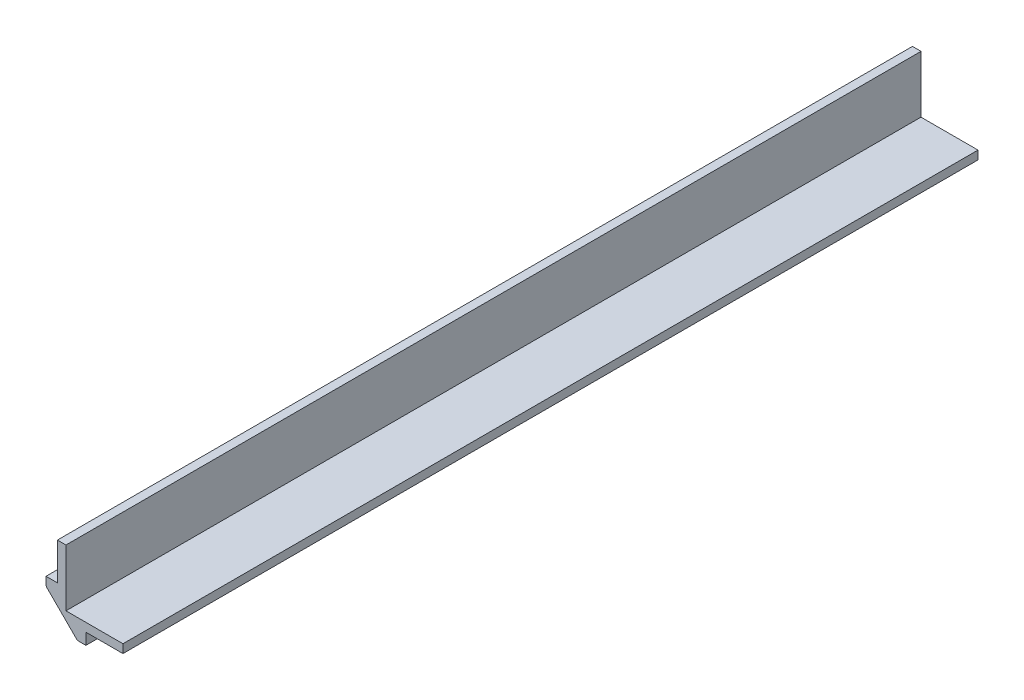
SolidWorks part; units mm, degrees
ref_plane "Front Plane" through (0, 0, 0) normal (0, 0, 1) x (1, 0, 0)
ref_plane "Top Plane" through (0, 0, 0) normal (0, 1, 0) x (1, 0, 0)
ref_plane "Right Plane" through (0, 0, 0) normal (1, 0, 0) x (0, 0, -1)
ref_plane "Plane1" through (0, 0, 280) normal (0, 0, 1) x (1, 0, 0)
sketch "Sketch1" plane through (0, 0, 280) normal (0, 0, 1) x (1, 0, 0)
  line L0 (-7, 4) -> (4, -7)
  line L1 (4, -7) -> (7, -7)
  line L2 (7, -7) -> (7, -3)
  line L3 (7, -3) -> (20, -3)
  line L4 (20, -3) -> (20, 0)
  line L5 (20, 0) -> (0, 0)
  line L6 (0, 0) -> (0, 20)
  line L7 (0, 20) -> (-3, 20)
  line L8 (-3, 20) -> (-3, 7)
  line L9 (-3, 7) -> (-7, 7)
  line L10 (-7, 7) -> (-7, 4)
extrude "Boss-Extrude1" add sketch "Sketch1" against normal blind 300
fillet "Fillet1" radius 1.5 2 edges at (-7, 4, 130) (4, -7, 130)
